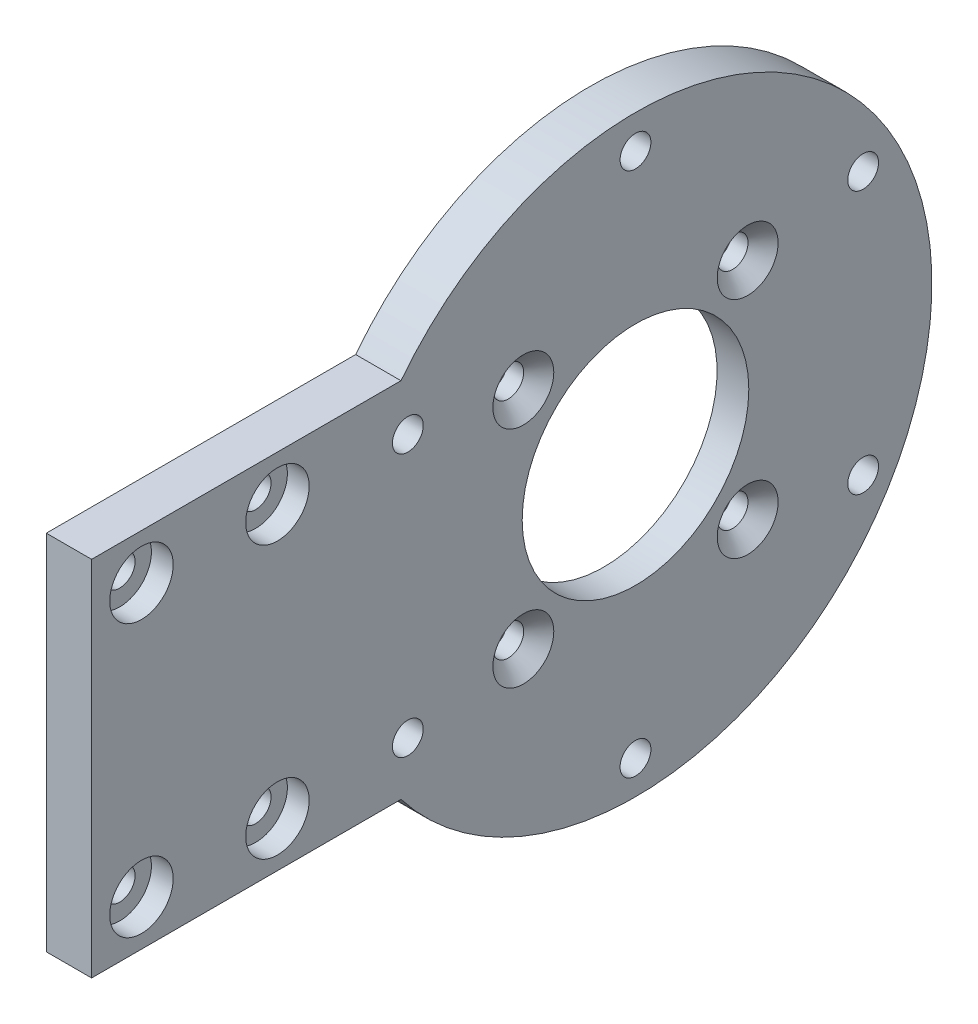
SolidWorks part; units mm, degrees
material "7075-O (SS)"
ref_plane "Front" through (0, 0, 0) normal (0, 0, 1) x (1, 0, 0)
ref_plane "Top" through (0, 0, 0) normal (0, 1, 0) x (1, 0, 0)
ref_plane "Right" through (0, 0, 0) normal (1, 0, 0) x (0, 0, -1)
sketch "Croquis1" plane through (0, 0, 0) normal (1, 0, 0) x (0, 0, -1)
  line L0 (-25.8706, 20) -> (-60, 20)
  line L1 (-60, 20) -> (-60, -20)
  line L2 (-60, -20) -> (-25.8706, -20)
  line L3 (2.75, 0) -> (-2.75, 0) construction
  line L4 (0, 2.75) -> (0, -2.75) construction
  arc A0 (-25.8706, -20) -> (-25.8706, 20) centre (0, 0) ccw
  circle A1 centre (0, 0) radius 12.5
  point P7 (-60, 0)
  dimension "D1" = 65.4
  dimension "D4" = 25
  dimension "D2" = 40
  dimension "D3" = 60
extrude "Saliente-Extruir1" add sketch "Croquis1" along normal mid plane 5
sketch "Croquis2" plane through (-2.5, 0, 0) normal (-1, 0, 0) x (0, 0, 1)
  circle A0 centre (0, 0) radius 21
  dimension "D1" = 42
extrude "Cortar-Extruir1" cut sketch "Croquis2" against normal blind 1.5
hole_wizard "Refrentado para tornillo tapón con cabeza plana de clavija de M31" positions "Croquis3" profile "Croquis5" countersink size "M3" standard "Ansi Metric"
sketch "Croquis3" plane through (2.5, 0, 0) normal (1, 0, 0) x (0, 0, -1)
  line L1 (-12.3744, -12.3744) -> (12.3744, -12.3744) construction
  line L2 (-12.3744, -12.3744) -> (-12.3744, 12.3744) construction
  line L3 (-12.3744, 12.3744) -> (12.3744, 12.3744) construction
  line L4 (12.3744, -12.3744) -> (12.3744, 12.3744) construction
  line L5 (-12.3744, -12.3744) -> (12.3744, 12.3744) construction
  line L6 (-12.3744, 12.3744) -> (12.3744, -12.3744) construction
  point P2 (12.3744, 12.3744)
  point P39 (-12.3744, -12.3744)
  point P40 (-12.3744, 12.3744)
  point P41 (12.3744, -12.3744)
  dimension "D1" = 35
sketch "Croquis5" plane through (2.5, 12.3744, -12.3744) normal (0, 1, 0) x (0, 0, -1)
  line L0 (0, 0) -> (0, 11.0215)
  line L1 (0, 11.0215) -> (1.7, 10)
  line L2 (1.7, 10) -> (1.7, 1.66)
  line L3 (1.7, 1.66) -> (3.36, 0)
  line L5 (3.36, 0) -> (0, 0)
  line L6 (-1.7, 1.66) -> (-3.36, 0) construction
  line L10 (0, 11.0215) -> (-1.7, 10) construction
  line L11 (0, -6.35) -> (0, 107.95) construction
  dimension "Diámetro de taladro" = 3.4
  dimension "Profundidad de taladro" = 10
  dimension "Ángulo de avellanado cercano" = 6.72
  dimension "Ángulo de avellanado lejano" = 90
  dimension "Ángulo de perforador" = 118
hole_wizard "Taladro de margen para M31" positions "Croquis6" profile "Croquis8" hole size "M3" standard "Ansi Metric" end condition through all
sketch "Croquis6" plane through (2.5, 0, 0) normal (1, 0, 0) x (0, 0, -1)
  line L0 (0, 2.75) -> (0, -2.75) construction
  line L1 (2.75, 0) -> (-2.75, 0) construction
  point P0 (0, 29)
  point P11 (25.1147, 14.5)
  point P12 (25.1147, -14.5)
  point P13 (0, -29)
  point P14 (-25.1147, -14.5)
  point P15 (-25.1147, 14.5)
  dimension "D1" = 29
  dimension "D3" = 29
  dimension "D2" = 6
sketch "Croquis8" plane through (2.5, 29, 0) normal (0, 1, 0) x (0, 0, -1)
  line L0 (0, 0) -> (0, 5)
  line L1 (0, 5) -> (1.7, 5)
  line L2 (1.7, 5) -> (1.7, 0)
  line L5 (1.7, 0) -> (0, 0)
  line L11 (0, -6.35) -> (0, 107.95) construction
  dimension "Diámetro de taladro hasta el siguiente" = 3.4
  dimension "Profundidad de taladro hasta el siguiente" = 5
hole_wizard "Refrentado para tornillo con cabeza troncocónica de M31" positions "Croquis9" profile "Croquis11" counterbore size "M3" standard "Ansi Metric" end condition through all
sketch "Croquis9" plane through (2.5, 0, 0) normal (1, 0, 0) x (0, 0, -1)
  line L1 (-54.5, -15) -> (-39.5, -15) construction
  line L2 (-54.5, -15) -> (-54.5, 15) construction
  line L3 (-54.5, 15) -> (-39.5, 15) construction
  line L4 (-39.5, -15) -> (-39.5, 15) construction
  line L5 (-54.5, -15) -> (-39.5, 15) construction
  line L6 (-54.5, 15) -> (-39.5, -15) construction
  line L8 (2.75, 0) -> (-2.75, 0) construction
  line L9 (-60, 20) -> (-60, -20) construction
  point P2 (-39.5, 15)
  point P63 (-54.5, -15)
  point P64 (-54.5, 15)
  point P65 (-39.5, -15)
  point P74 (-47, 0)
  dimension "D1" = 30
  dimension "D2" = 15
  dimension "D3" = 13
sketch "Croquis11" plane through (2.5, 15, 39.5) normal (0, 1, 0) x (0, 0, -1)
  line L0 (0, 0) -> (0, 5)
  line L1 (0, 5) -> (1.7, 5)
  line L3 (1.7, 5) -> (1.7, 2.4)
  line L4 (1.7, 2.4) -> (3.5, 2.4)
  line L5 (3.5, 2.4) -> (3.5, 0)
  line L7 (3.5, 0) -> (0, 0)
  line L11 (0, -6.35) -> (0, 107.95) construction
  dimension "Diámetro de taladro hasta el siguiente" = 3.4
  dimension "Profundidad de taladro hasta el siguiente" = 5
  dimension "Diámetro de refrentado" = 7
  dimension "Profundidad de refrentado" = 2.4
